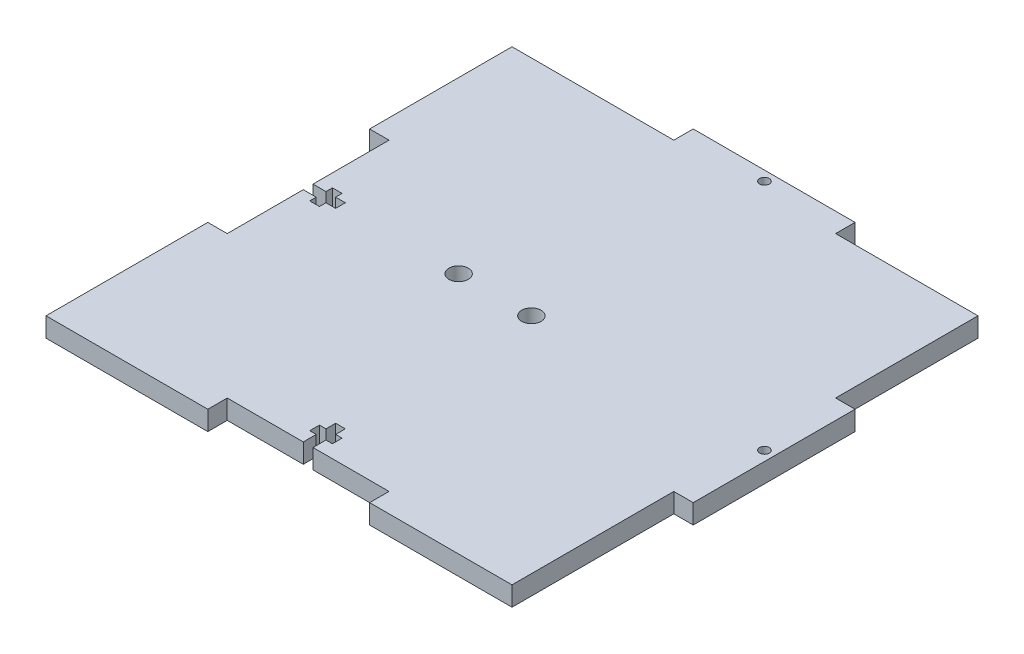
SolidWorks part; units mm, degrees
material "Acrylic (Medium-high impact)"
ref_plane "Front Plane" through (0, 0, 0) normal (0, 0, 1) x (1, 0, 0)
ref_plane "Top Plane" through (0, 0, 0) normal (0, 1, 0) x (1, 0, 0)
ref_plane "Right Plane" through (0, 0, 0) normal (1, 0, 0) x (0, 0, -1)
sketch "Sketch1" plane through (0, 0, 0) normal (0, 1, 0) x (1, 0, 0)
  line L0 (-72, 28) -> (-66, 28)
  line L1 (-72, -72) -> (72, -72)
  line L2 (-72, -72) -> (-72, 72)
  line L3 (-72, 72) -> (72, 72)
  line L4 (72, -72) -> (72, 72)
  line L5 (-72, -72) -> (72, 72) construction
  line L6 (-72, 72) -> (72, -72) construction
  line L7 (-66, 28) -> (-66, -22)
  line L8 (28, -72) -> (28, -66)
  line L9 (-22, 72) -> (-22, 78)
  line L10 (-22, 78) -> (28, 78)
  line L11 (28, 72) -> (28, 78)
  line L12 (72, 28) -> (78, 28)
  line L13 (78, 28) -> (78, -22)
  line L14 (-22, -72) -> (-22, -66)
  line L15 (-22, -66) -> (28, -66)
  line L16 (3, 78) -> (3, -72) construction
  line L17 (-72, 3) -> (78, 3) construction
  line L18 (72, -22) -> (78, -22)
  line L19 (-72, -22) -> (-66, -22)
  line L20 (75, 28) -> (75, -22) construction
  line L21 (4.5, -66) -> (4.5, -62)
  line L22 (4.5, -62) -> (6.5, -62)
  line L23 (6.5, -62) -> (6.5, -59)
  line L24 (6.5, -59) -> (4.5, -59)
  line L25 (4.5, -59) -> (4.5, -56)
  line L26 (4.5, -56) -> (1.5, -56)
  line L27 (1.5, -66) -> (1.5, -62)
  line L28 (1.5, -62) -> (-0.5, -62)
  line L29 (-0.5, -59) -> (1.5, -59)
  line L30 (-0.5, -62) -> (-0.5, -59)
  line L31 (1.5, -59) -> (1.5, -56)
  line L32 (-59, 4.5) -> (-56, 4.5)
  line L33 (-62, 4.5) -> (-62, 6.5)
  line L34 (-59, 6.5) -> (-59, 4.5)
  line L35 (-62, 6.5) -> (-59, 6.5)
  line L36 (-66, 4.5) -> (-62, 4.5)
  line L37 (-66, 1.5) -> (-62, 1.5)
  line L38 (-62, 1.5) -> (-62, -0.5)
  line L39 (-62, -0.5) -> (-59, -0.5)
  line L40 (-59, -0.5) -> (-59, 1.5)
  line L41 (-59, 1.5) -> (-56, 1.5)
  line L42 (-56, 4.5) -> (-56, 1.5)
  circle A0 centre (75, 3) radius 1.5
  circle A1 centre (3, 75) radius 1.5
  circle A2 centre (3, 3) radius 3
  circle A4 centre (-19.5, 3) radius 3
  point P0 (0, 0)
  point P22 (3, 3)
  point P27 (3, 3)
  point P40 (3, -66)
  point P45 (-66, 3)
  point P49 (3, -56)
  dimension "D4" = 3
  dimension "D9" = 6
  dimension "D1" = 144
  dimension "D2" = 25
  dimension "D3" = 6
  dimension "D5" = 4
  dimension "D6" = 2
  dimension "D7" = 3
  dimension "D8" = 1.5
  dimension "D10" = 2
extrude "Boss-Extrude1" add sketch "Sketch1" along normal blind 6 contours L19 L2 L1 L14 L15 L8 L4 L3 L0 L7 | L3 L11 L10 L9 | L4 L18 L13 L12
